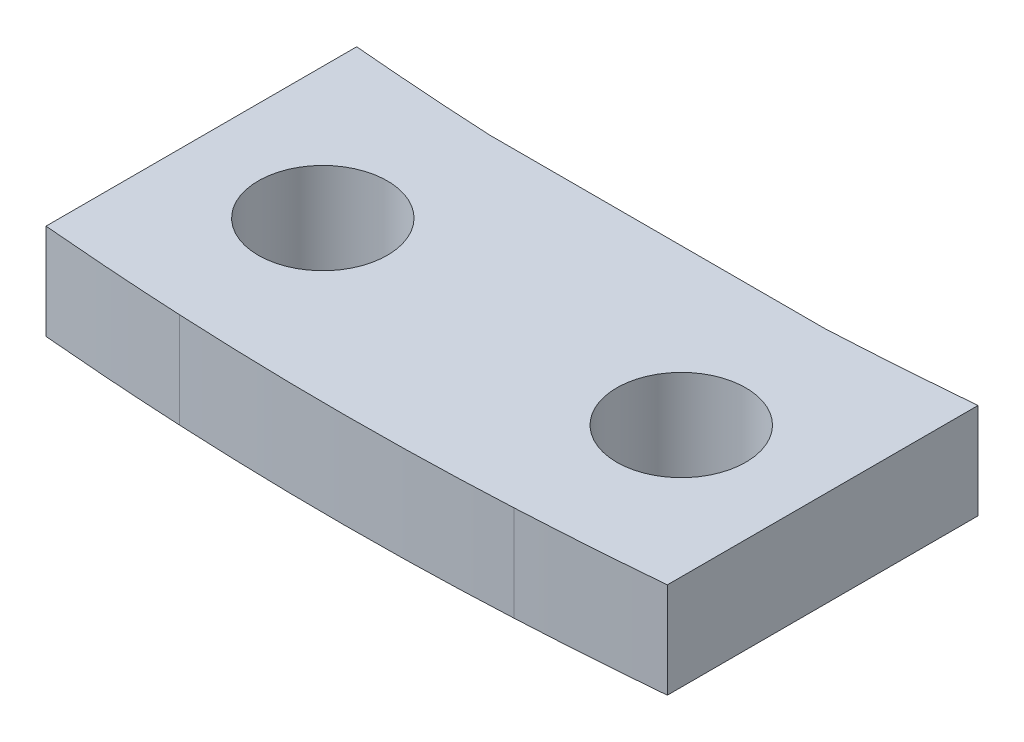
SolidWorks part; units mm, degrees
material "PLA Black"
ref_plane "Front" through (0, 0, 0) normal (0, 0, 1) x (1, 0, 0)
ref_plane "Top" through (0, 0, 0) normal (0, 1, 0) x (1, 0, 0)
ref_plane "Right" through (0, 0, 0) normal (1, 0, 0) x (0, 0, -1)
sketch "Sketch1" plane through (0, 0, 0) normal (0, 1, 0) x (1, 0, 0)
  line L0 (13, 6.9166) -> (13, -6.0834) construction
  line L1 (-13, 6.9166) -> (-13, -6.0834) construction
  line L2 (13, 6.9166) -> (13, -6.0834)
  line L3 (-13, 6.9166) -> (-13, -6.0834)
  line L4 (7, 6.5) -> (-7, 6.5)
  circle A0 centre (-7.5, 0) radius 2.7 construction
  circle A1 centre (7.5, 0) radius 2.7 construction
  circle A2 centre (-7.5, 0) radius 2.7
  circle A3 centre (7.5, 0) radius 2.7
  spline S0 degree 3 poles (325.3477, 1955.1118) (234.3173, 106.9806) (-38.4724, -155.9256) (-273.6727, 188.3757) (297.2884, -1972.8102) knots -58.599019 -58.599019 -58.599019 -58.599019 0.56 69.101968 69.101968 69.101968 69.101968 only from (-7, -6.5) to (-13, -6.0834) construction
  spline S1 degree 3 poles (-1989.5255, 110.3845) (-574.1815, 36.3768) (91.1587, -2.5928) (5.3504, -6.5775) (3.1788, -6.6521) (1.021, -6.6761) (-0.2785, -6.6761) (-1.579, -6.6721) (-3.7404, -6.635) (-5.6325, -6.5644) (-91.1673, -2.5924) (574.157, 36.3933) (1989.4775, 110.4328) knots -17.975157 -17.975157 -17.975157 -17.975157 0.036448 0.036448 0.28 0.5 0.5 0.56 0.78 0.963553 0.963553 18.977167 18.977167 18.977167 18.977167 only from (7, -6.5) to (-7, -6.5) construction
  spline S2 degree 3 poles (-9.6299, -1994.2995) (275.0411, 194.5582) (39.0456, -161.0119) (-235.1812, 111.2357) (-118.4215, 1977.896) knots -68.551071 -68.551071 -68.551071 -68.551071 0.56 59.721233 59.721233 59.721233 59.721233 only from (13, -6.0834) to (7, -6.5) construction
  spline S3 degree 3 poles (-7, -6.5) (-8.1213, -6.4441) (-10.1224, -6.3209) (-12.1212, -6.1605) (-13, -6.0834) knots 0 0 0 0 0.56 1 1 1 1
  spline S4 degree 3 poles (7, -6.5) (6.8348, -6.5082) (6.6666, -6.5163) (5.3504, -6.5775) (3.1788, -6.6521) (1.021, -6.6761) (-0.2785, -6.6761) (-1.579, -6.6721) (-3.7404, -6.635) (-5.6325, -6.5644) (-6.6666, -6.5163) (-6.8348, -6.5082) (-7, -6.5) knots 0 0 0 0 0.036448 0.036448 0.28 0.5 0.5 0.56 0.78 0.963553 0.963553 1 1 1 1
  spline S5 degree 3 poles (13, -6.0834) (11.8815, -6.1815) (9.8824, -6.3379) (7.881, -6.4561) (7, -6.5) knots 0 0 0 0 0.56 1 1 1 1
  spline S6 degree 3 poles (9.6299, -1981.2995) (-518.7283, 2081.2887) (371.5778, -2056.3627) (118.4215, 1990.896) knots -15.835168 -15.835168 -15.835168 -15.835168 13.795492 13.795492 13.795492 13.795492 only from (-13, 6.9166) to (-7, 6.5) construction
  spline S7 degree 3 poles (-118.4185, 1990.9443) (-371.5849, -2056.3957) (518.7304, 2081.305) (-9.6299, -1981.2997) knots -12.79561 -12.79561 -12.79561 -12.79561 16.835168 16.835168 16.835168 16.835168 only from (7, 6.5) to (13, 6.9166) construction
  spline S8 degree 3 poles (-13, 6.9166) (-11.0026, 6.7413) (-9.0022, 6.5999) (-7, 6.5) knots 0 0 0 0 0.230998 0.230998 0.230998 0.230998
  spline S9 degree 3 poles (7, 6.5) (9.0022, 6.5999) (11.0026, 6.7413) (13, 6.9166) knots 0.769002 0.769002 0.769002 0.769002 1 1 1 1
extrude "Boss-Extrude1" add sketch "Sketch1" along normal blind 4
